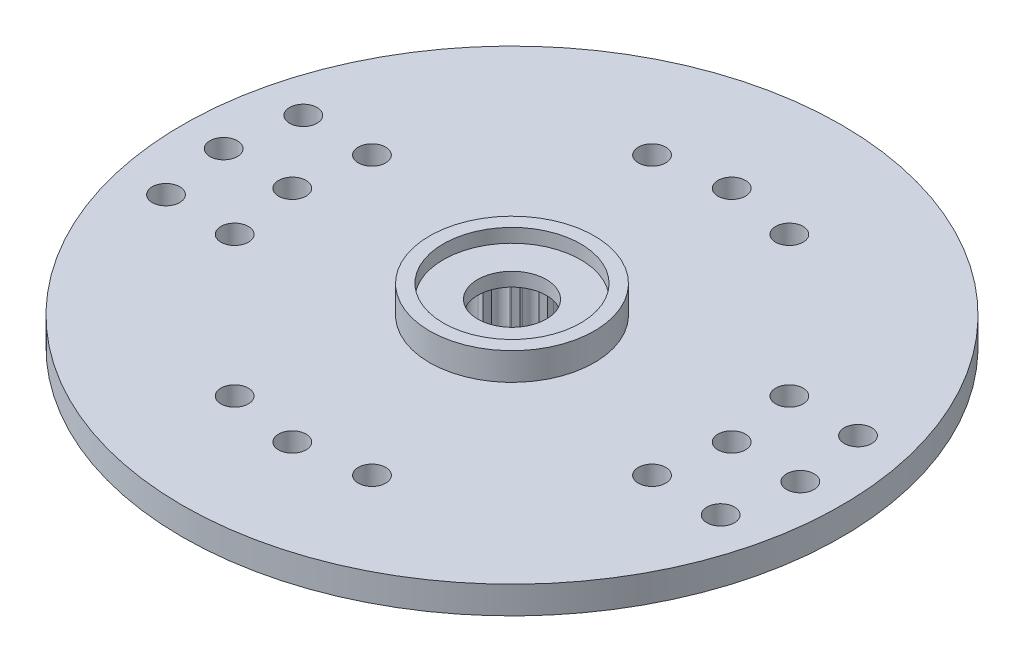
SolidWorks part; units mm, degrees
material "PP Homopolymer"
ref_plane "Front Plane" through (0, 0, 0) normal (0, 0, 1) x (1, 0, 0)
ref_plane "Top Plane" through (0, 0, 0) normal (0, 1, 0) x (1, 0, 0)
ref_plane "Right Plane" through (0, 0, 0) normal (1, 0, 0) x (0, 0, -1)
sketch "Sketch1" plane through (0, 0, 0) normal (0, 1, 0) x (1, 0, 0)
  circle A0 centre (0, 0) radius 5
  dimension "D1" = 10
extrude "Boss-Extrude1" add sketch "Sketch1" along normal blind 2
sketch "Sketch2" plane through (0, 2, 0) normal (0, 1, 0) x (1, 0, 0)
  circle A0 centre (0, 0) radius 12
  dimension "D1" = 24
extrude "Boss-Extrude2" add sketch "Sketch2" along normal blind 2
sketch "Sketch3" plane through (0, 0, 0) normal (0, -1, 0) x (1, 0, 0)
  circle A0 centre (0, 0) radius 1.25
  dimension "D1" = 2.5
extrude "Cut-Extrude1" cut sketch "Sketch3" against normal through all
sketch "Sketch4" plane through (0, 0, 0) normal (0, -1, 0) x (1, 0, 0)
  line L0 (0.25, 2.25) -> (0.25, 1.9843)
  line L1 (-0.25, 2.25) -> (-0.25, 1.9843)
  line L2 (0, 2.25) -> (0, 0) construction
  line L3 (1.0459, 2.0078) -> (0.9499, 1.76)
  line L4 (0.5797, 2.1884) -> (0.4837, 1.9406)
  line L5 (1.7006, 1.4943) -> (1.5216, 1.298)
  line L6 (1.3311, 1.8312) -> (1.1521, 1.6348)
  line L7 (2.1256, 0.7791) -> (1.8877, 0.6607)
  line L8 (1.9027, 1.2267) -> (1.6648, 1.1083)
  line L9 (2.2635, -0.0413) -> (1.9989, -0.0658)
  line L10 (2.2173, 0.4565) -> (1.9528, 0.432)
  line L11 (2.0957, -0.8562) -> (1.8401, -0.7835)
  line L12 (2.2325, -0.3753) -> (1.977, -0.3026)
  line L13 (1.6449, -1.5554) -> (1.4329, -1.3953)
  line L14 (1.9462, -1.1564) -> (1.7342, -0.9963)
  line L15 (0.9719, -2.0446) -> (0.8321, -1.8187)
  line L16 (1.397, -1.7814) -> (1.2572, -1.5555)
  line L17 (0.1677, -2.2576) -> (0.1189, -1.9965)
  line L18 (0.6592, -2.1658) -> (0.6104, -1.9046)
  line L19 (-0.6592, -2.1658) -> (-0.6104, -1.9046)
  line L20 (-0.1677, -2.2576) -> (-0.1189, -1.9965)
  line L21 (-1.397, -1.7814) -> (-1.2572, -1.5555)
  line L22 (-0.9719, -2.0446) -> (-0.8321, -1.8187)
  line L23 (-1.9462, -1.1564) -> (-1.7342, -0.9963)
  line L24 (-1.6449, -1.5554) -> (-1.4329, -1.3953)
  line L25 (-2.2325, -0.3753) -> (-1.977, -0.3026)
  line L26 (-2.0957, -0.8562) -> (-1.8401, -0.7835)
  line L27 (-2.2173, 0.4565) -> (-1.9528, 0.432)
  line L28 (-2.2635, -0.0413) -> (-1.9989, -0.0658)
  line L29 (-1.9027, 1.2267) -> (-1.6648, 1.1083)
  line L30 (-2.1256, 0.7791) -> (-1.8877, 0.6607)
  line L31 (-1.3311, 1.8312) -> (-1.1521, 1.6348)
  line L32 (-1.7006, 1.4943) -> (-1.5216, 1.298)
  line L33 (-0.5797, 2.1884) -> (-0.4837, 1.9406)
  line L34 (-1.0459, 2.0078) -> (-0.9499, 1.76)
  arc A0 (-0.25, 1.9843) -> (-0.4837, 1.9406) centre (0, 0) ccw
  arc A1 (0.25, 2.25) -> (-0.25, 2.25) centre (0, 2.25) ccw
  arc A2 (1.0459, 2.0078) -> (0.5797, 2.1884) centre (0.8128, 2.0981) ccw
  arc A3 (1.7006, 1.4943) -> (1.3311, 1.8312) centre (1.5158, 1.6628) ccw
  arc A4 (2.1256, 0.7791) -> (1.9027, 1.2267) centre (2.0141, 1.0029) ccw
  arc A5 (2.2635, -0.0413) -> (2.2173, 0.4565) centre (2.2404, 0.2076) ccw
  arc A6 (2.0957, -0.8562) -> (2.2325, -0.3753) centre (2.1641, -0.6157) ccw
  arc A7 (1.6449, -1.5554) -> (1.9462, -1.1564) centre (1.7955, -1.3559) ccw
  arc A8 (0.9719, -2.0446) -> (1.397, -1.7814) centre (1.1845, -1.913) ccw
  arc A9 (0.1677, -2.2576) -> (0.6592, -2.1658) centre (0.4134, -2.2117) ccw
  arc A10 (-0.6592, -2.1658) -> (-0.1677, -2.2576) centre (-0.4134, -2.2117) ccw
  arc A11 (-1.397, -1.7814) -> (-0.9719, -2.0446) centre (-1.1845, -1.913) ccw
  arc A12 (-1.9462, -1.1564) -> (-1.6449, -1.5554) centre (-1.7955, -1.3559) ccw
  arc A13 (-2.2325, -0.3753) -> (-2.0957, -0.8562) centre (-2.1641, -0.6157) ccw
  arc A14 (-2.2173, 0.4565) -> (-2.2635, -0.0413) centre (-2.2404, 0.2076) ccw
  arc A15 (-1.9027, 1.2267) -> (-2.1256, 0.7791) centre (-2.0141, 1.0029) ccw
  arc A16 (-1.3311, 1.8312) -> (-1.7006, 1.4943) centre (-1.5158, 1.6628) ccw
  arc A17 (-0.5797, 2.1884) -> (-1.0459, 2.0078) centre (-0.8128, 2.0981) ccw
  arc A18 (0.4837, 1.9406) -> (0.25, 1.9843) centre (0, 0) ccw
  arc A19 (1.1521, 1.6348) -> (0.9499, 1.76) centre (0, 0) ccw
  arc A20 (1.6648, 1.1083) -> (1.5216, 1.298) centre (0, 0) ccw
  arc A21 (1.9528, 0.432) -> (1.8877, 0.6607) centre (0, 0) ccw
  arc A22 (1.977, -0.3026) -> (1.9989, -0.0658) centre (0, 0) ccw
  arc A23 (1.7342, -0.9963) -> (1.8401, -0.7835) centre (0, 0) ccw
  arc A24 (1.2572, -1.5555) -> (1.4329, -1.3953) centre (0, 0) ccw
  arc A25 (0.6104, -1.9046) -> (0.8321, -1.8187) centre (0, 0) ccw
  arc A26 (-0.1189, -1.9965) -> (0.1189, -1.9965) centre (0, 0) ccw
  arc A27 (-0.8321, -1.8187) -> (-0.6104, -1.9046) centre (0, 0) ccw
  arc A28 (-1.4329, -1.3953) -> (-1.2572, -1.5555) centre (0, 0) ccw
  arc A29 (-1.8401, -0.7835) -> (-1.7342, -0.9963) centre (0, 0) ccw
  arc A30 (-1.9989, -0.0658) -> (-1.977, -0.3026) centre (0, 0) ccw
  arc A31 (-1.8877, 0.6607) -> (-1.9528, 0.432) centre (0, 0) ccw
  arc A32 (-1.5216, 1.298) -> (-1.6648, 1.1083) centre (0, 0) ccw
  arc A33 (-0.9499, 1.76) -> (-1.1521, 1.6348) centre (0, 0) ccw
  point P89 (0, 0)
  dimension "D2" = 0.5
  dimension "D3" = 2.25
  dimension "D4" = 17
extrude "Cut-Extrude2" cut sketch "Sketch4" against normal blind 3
sketch "Sketch5" plane through (0, 4, 0) normal (0, 1, 0) x (1, 0, 0)
  circle A0 centre (0, 0) radius 3
  circle A2 centre (0, 0) radius 12
  dimension "D1" = 6
  dimension "D3" = 24
extrude "Cut-Extrude3" cut sketch "Sketch5" against normal blind 1
sketch "Sketch6" plane through (0, 4, 0) normal (0, 1, 0) x (1, 0, 0)
  circle A0 centre (0, 0) radius 2.5
  circle A1 centre (0, 0) radius 3 construction
  dimension "D1" = 0.5
extrude "Cut-Extrude4" cut sketch "Sketch6" against normal blind 0.5
sketch "Sketch7" plane through (0, 2, 0) normal (0, -1, 0) x (1, 0, 0)
  circle A0 centre (0, 0) radius 8 construction
  circle A1 centre (0, 0) radius 12 construction
  circle A2 centre (0, 8) radius 0.5
  circle A3 centre (2.5, 7.5993) radius 0.5
  circle A4 centre (-2.5, 7.5993) radius 0.5
  circle A5 centre (8, 0) radius 0.5
  circle A6 centre (7.5993, -2.5) radius 0.5
  circle A7 centre (7.5993, 2.5) radius 0.5
  circle A8 centre (0, -8) radius 0.5
  circle A9 centre (-2.5, -7.5993) radius 0.5
  circle A10 centre (2.5, -7.5993) radius 0.5
  circle A11 centre (-8, 0) radius 0.5
  circle A12 centre (-7.5993, 2.5) radius 0.5
  circle A13 centre (-7.5993, -2.5) radius 0.5
  circle A14 centre (0, 0) radius 10.5 construction
  circle A15 centre (10.0993, 2.5) radius 0.5
  circle A16 centre (10.0993, -2.5) radius 0.5
  circle A17 centre (10.5, 0) radius 0.5
  circle A18 centre (-10.0993, 2.5) radius 0.5
  circle A19 centre (-10.0993, -2.5) radius 0.5
  circle A20 centre (-10.5, 0) radius 0.5
  point P32 (0, 0)
  dimension "D1" = 4
  dimension "D2" = 1
  dimension "D3" = 2.5
  dimension "D4" = 2.5
  dimension "D6" = 21
  dimension "D5" = 4
extrude "Cut-Extrude5" cut sketch "Sketch7" against normal through all
